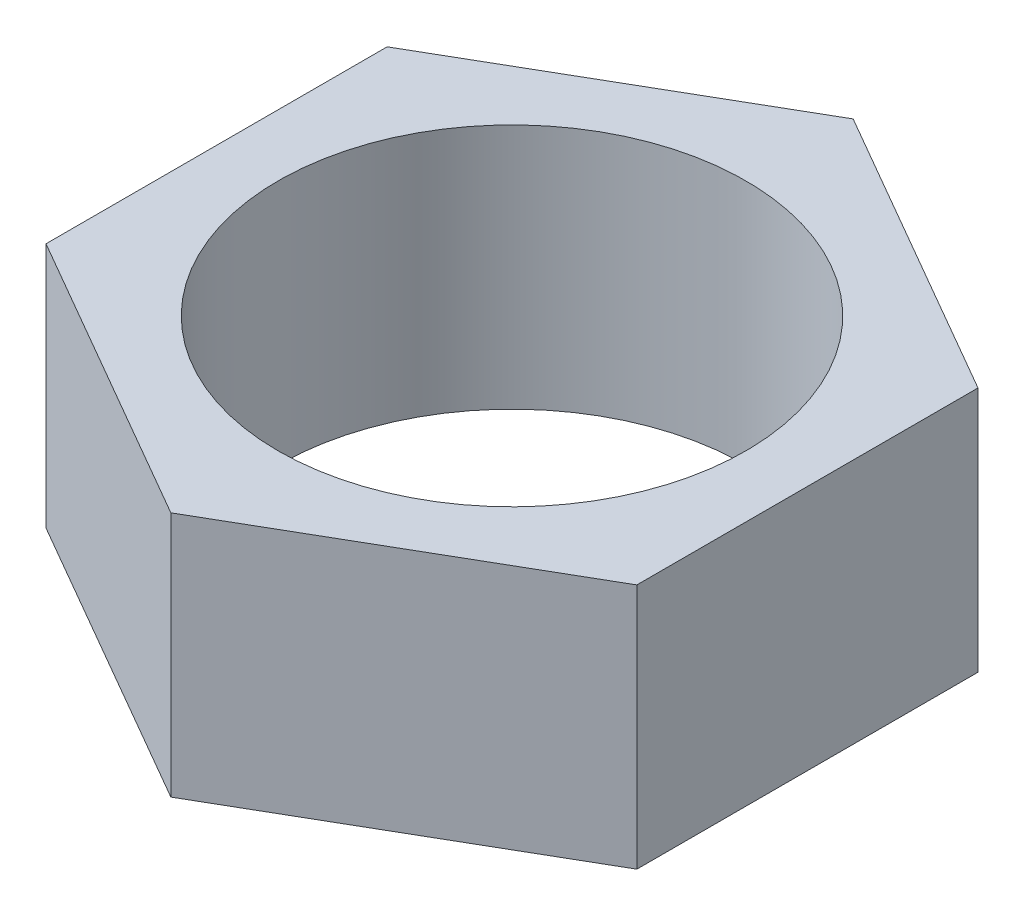
SolidWorks part; units mm, degrees
ref_plane "Front Plane" through (0, 0, 0) normal (0, 0, 1) x (1, 0, 0)
ref_plane "Top Plane" through (0, 0, 0) normal (0, 1, 0) x (1, 0, 0)
ref_plane "Right Plane" through (0, 0, 0) normal (1, 0, 0) x (0, 0, -1)
sketch "Sketch1" plane through (0, 0, 0) normal (0, 1, 0) x (1, 0, 0)
  line L1 (-3.048, 1.7598) -> (-3.048, -1.7598)
  line L2 (-3.048, -1.7598) -> (0, -3.5195)
  line L3 (0, -3.5195) -> (3.048, -1.7598)
  line L4 (3.048, -1.7598) -> (3.048, 1.7598)
  line L5 (3.048, 1.7598) -> (0, 3.5195)
  line L6 (0, 3.5195) -> (-3.048, 1.7598)
  circle A0 centre (0, 0) radius 3.048 construction
  circle A1 centre (0, 0) radius 2.413
  dimension "D1" = 6.096
  dimension "D2" = 4.826
extrude "Boss-Extrude2" add sketch "Sketch1" along normal blind 2.54
